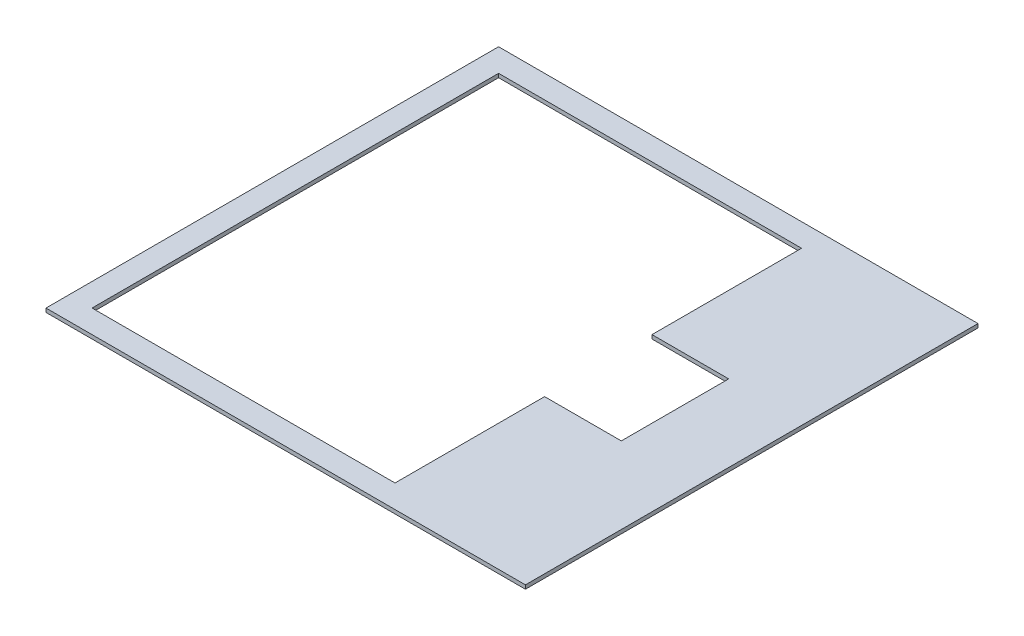
SolidWorks part; units mm, degrees
ref_plane "Front Plane" through (0, 0, 0) normal (0, 0, 1) x (1, 0, 0)
ref_plane "Top Plane" through (0, 0, 0) normal (0, 1, 0) x (1, 0, 0)
ref_plane "Right Plane" through (0, 0, 0) normal (1, 0, 0) x (0, 0, -1)
sketch "Sketch1" plane through (0, 0, 0) normal (0, 1, 0) x (1, 0, 0)
  line L1 (-312.5, 295) -> (312.5, 295)
  line L2 (-312.5, 295) -> (-312.5, -295)
  line L3 (-312.5, -295) -> (312.5, -295)
  line L4 (312.5, 295) -> (312.5, -295)
  line L5 (-312.5, 295) -> (312.5, -295) construction
  line L6 (-312.5, -295) -> (312.5, 295) construction
  point P0 (0, 0)
extrude "Boss-Extrude1" add sketch "Sketch1" along normal blind 5
sketch "Sketch2" plane through (0, 5, 0) normal (0, 1, 0) x (1, 0, 0)
  line L0 (-312.5, 295) -> (-282.5, 295)
  line L1 (312.5, 295) -> (-312.5, 295) construction
  line L2 (-282.5, 295) -> (-282.5, -295)
  line L3 (-312.5, -295) -> (312.5, -295) construction
  line L4 (312.5, 295) -> (112.5, 295)
  line L5 (112.5, 295) -> (112.5, -295)
  line L6 (112.5, -295) -> (312.5, -295)
  line L7 (312.5, -295) -> (312.5, 295)
  line L8 (-282.5, 295) -> (112.5, 295)
  line L9 (-282.5, -295) -> (112.5, -295)
  line L10 (-312.5, 295) -> (-312.5, 265)
  line L11 (-312.5, 295) -> (-312.5, -295) construction
  line L12 (-312.5, -295) -> (-312.5, -265)
  line L13 (-312.5, 265) -> (112.5, 265)
  line L14 (-312.5, -265) -> (112.5, -265)
  line L15 (-312.5, 265) -> (-282.5, 265)
  line L17 (-282.5, 265) -> (112.5, 265)
  line L18 (-282.5, 265) -> (-282.5, -265)
  line L19 (-282.5, -265) -> (112.5, -265)
  line L20 (112.5, 265) -> (112.5, -265)
extrude "Cut-Extrude1" cut sketch "Sketch2" against normal blind 23.4 contours L2 L14 L5 L13
sketch "Sketch3" plane through (0, 5, 0) normal (0, 1, 0) x (1, 0, 0)
  line L0 (112.5, 0) -> (112.5, -70)
  line L3 (112.5, 0) -> (112.5, 70)
  line L4 (112.5, 265) -> (112.5, -265) construction
  line L5 (112.5, 70) -> (212.5, 70)
  line L6 (112.5, -70) -> (212.5, -70)
  line L7 (212.5, -70) -> (212.5, 70)
  line L8 (112.5, 70) -> (212.5, 70)
  line L9 (112.5, 70) -> (112.5, -70)
  line L10 (112.5, -70) -> (212.5, -70)
  line L11 (212.5, 70) -> (212.5, -70)
  line M6 (112.5, 265) -> (112.5, -265)
extrude "Cut-Extrude2" cut sketch "Sketch3" against normal blind 23.4 contours L6 L7 L5 M6
